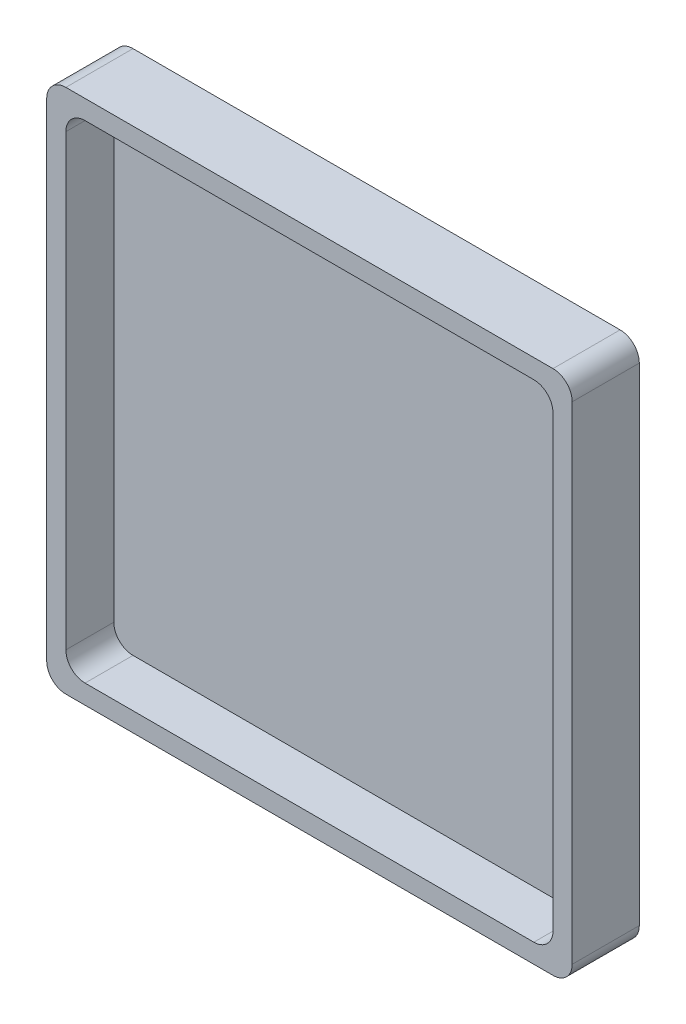
SolidWorks part; units mm, degrees
material "Custom Plastic"
ref_plane "X-Y Datum" through (0, 0, 0) normal (0, 0, 1) x (1, 0, 0)
ref_plane "X-Z Datum" through (0, 0, 0) normal (0, 1, 0) x (1, 0, 0)
ref_plane "Y-Z Datum" through (0, 0, 0) normal (1, 0, 0) x (0, 0, -1)
sketch "Sketch1" plane through (0, 0, 0) normal (0, 0, 1) x (1, 0, 0)
  line L0 (-27.4, 27.4) -> (-27.4, -27.4)
  line L1 (-25.4, 25.4) -> (25.4, 25.4)
  line L2 (-25.4, 25.4) -> (-25.4, -25.4)
  line L3 (-25.4, -25.4) -> (25.4, -25.4)
  line L4 (25.4, 25.4) -> (25.4, -25.4)
  line L5 (-25.4, 25.4) -> (25.4, -25.4) construction
  line L6 (-25.4, -25.4) -> (25.4, 25.4) construction
  line L7 (-27.4, -27.4) -> (27.4, -27.4)
  line L8 (27.4, 27.4) -> (27.4, -27.4)
  line L9 (-27.4, 27.4) -> (27.4, 27.4)
  point P0 (0, 0)
  dimension "D1" = 50.8
  dimension "D2" = 50.8
  dimension "D3" = 2
extrude "Boss-Extrude1" add sketch "Sketch1" along normal blind 2 contours L4 L1 L2 L3 | L9 L0 L7 L8 L1 L4 L3 L2
sketch "Sketch2" plane through (0, 0, 2) normal (0, 0, 1) x (1, 0, 0)
  line L4 (25.4, 25.4) -> (-25.4, 25.4)
  line L5 (25.4, -25.4) -> (25.4, 25.4)
  line L6 (-25.4, -25.4) -> (25.4, -25.4)
  line L7 (-25.4, 25.4) -> (-25.4, -25.4)
  line L8 (25.4, 25.4) -> (-25.4, 25.4)
  line L9 (25.4, -25.4) -> (25.4, 25.4)
  line L10 (-25.4, -25.4) -> (25.4, -25.4)
  line L11 (-25.4, 25.4) -> (-25.4, -25.4)
  line L12 (-27.4, 27.4) -> (-27.4, -27.4)
  line L13 (-27.4, -27.4) -> (27.4, -27.4)
  line L14 (27.4, -27.4) -> (27.4, 27.4)
  line L15 (27.4, 27.4) -> (-27.4, 27.4)
  line L16 (-27.4, 27.4) -> (-27.4, -27.4)
  line L17 (-27.4, -27.4) -> (27.4, -27.4)
  line L18 (27.4, -27.4) -> (27.4, 27.4)
  line L19 (27.4, 27.4) -> (-27.4, 27.4)
  dimension "D1" = 0
  dimension "D2" = 0
extrude "Boss-Extrude2" add sketch "Sketch2" along normal blind 5
fillet "Fillet1" radius 2 8 edges at (25.4, -25.4, 4.5) (-25.4, -25.4, 4.5) (-25.4, 25.4, 4.5) (25.4, 25.4, 4.5) (27.4, 27.4, 3.5) (-27.4, 27.4, 3.5) (-27.4, -27.4, 3.5) (27.4, -27.4, 3.5)
